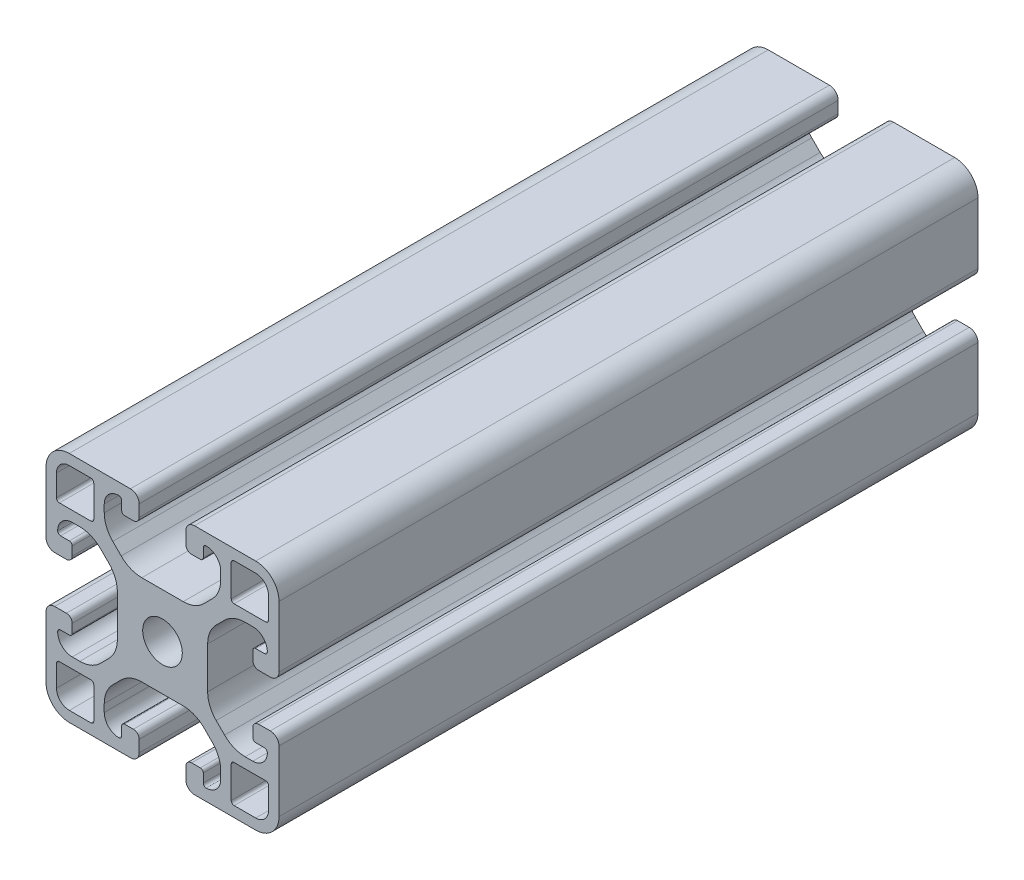
SolidWorks part; units mm, degrees
ref_plane "Plan de face" through (0, 0, 0) normal (0, 0, 1) x (1, 0, 0)
ref_plane "Plan de dessus" through (0, 0, 0) normal (0, 1, 0) x (1, 0, 0)
ref_plane "Plan de droite" through (0, 0, 0) normal (1, 0, 0) x (0, 0, -1)
ref_plane "Plan1" through (0, 0, -30) normal (0, 0, -1) x (-1, 0, 0)
sketch "Esquisse1" plane through (0, 0, -30) normal (0, 0, -1) x (-1, 0, 0)
  line L0 (-4.5, 15) -> (-4.5, 13.5)
  line L1 (-4, 13) -> (-2.5, 13)
  line L2 (-4.5, 10) -> (-5.8076, 10)
  line L3 (-9.3431, 11.4645) -> (-10.7855, 12.9069)
  line L4 (-12.25, 16.4424) -> (-12.25, 23.5576)
  line L5 (-10.7855, 27.0931) -> (-9.3431, 28.5355)
  line L6 (-5.8076, 30) -> (-4.5, 30)
  line L7 (-2.5, 27) -> (-4, 27)
  line L8 (-4.5, 26.5) -> (-4.5, 25)
  line L9 (-3.5, 24) -> (-1.5, 24)
  line L10 (0, 25.5) -> (0, 36)
  line L11 (-4, 40) -> (-14.5, 40)
  line L12 (-16, 38.5) -> (-16, 36.5)
  line L13 (-15, 35.5) -> (-13.5, 35.5)
  line L14 (-13, 36) -> (-13, 37.5)
  line L15 (-10, 35.5) -> (-10, 34.1924)
  line L16 (-11.4645, 30.6569) -> (-12.9069, 29.2145)
  line L17 (-16.4424, 27.75) -> (-23.5576, 27.75)
  line L18 (-27.0931, 29.2145) -> (-28.5355, 30.6569)
  line L19 (-30, 34.1924) -> (-30, 35.5)
  line L20 (-27, 37.5) -> (-27, 36)
  line L21 (-26.5, 35.5) -> (-25, 35.5)
  line L22 (-24, 36.5) -> (-24, 38.5)
  line L23 (-25.5, 40) -> (-36, 40)
  line L24 (-40, 36) -> (-40, 25.5)
  line L25 (-38.5, 24) -> (-36.5, 24)
  line L26 (-35.5, 25) -> (-35.5, 26.5)
  line L27 (-36, 27) -> (-37.5, 27)
  line L28 (-35.5, 30) -> (-34.1924, 30)
  line L29 (-30.6569, 28.5355) -> (-29.2145, 27.0931)
  line L30 (-27.75, 23.5576) -> (-27.75, 16.4424)
  line L31 (-29.2145, 12.9069) -> (-30.6569, 11.4645)
  line L32 (-34.1924, 10) -> (-35.5, 10)
  line L33 (-37.5, 13) -> (-36, 13)
  line L34 (-35.5, 13.5) -> (-35.5, 15)
  line L35 (-36.5, 16) -> (-38.5, 16)
  line L36 (-40, 14.5) -> (-40, 4)
  line L37 (-36, 0) -> (-25.5, 0)
  line L38 (-24, 1.5) -> (-24, 3.5)
  line L39 (-25, 4.5) -> (-26.5, 4.5)
  line L40 (-27, 4) -> (-27, 2.5)
  line L41 (-30, 4.5) -> (-30, 5.8076)
  line L42 (-28.5355, 9.3431) -> (-27.0931, 10.7855)
  line L43 (-23.5576, 12.25) -> (-16.4424, 12.25)
  line L44 (-12.9069, 10.7855) -> (-11.4645, 9.3431)
  line L45 (-10, 5.8076) -> (-10, 4.5)
  line L46 (-13, 2.5) -> (-13, 4)
  line L47 (-13.5, 4.5) -> (-15, 4.5)
  line L48 (-16, 3.5) -> (-16, 1.5)
  line L49 (-14.5, 0) -> (-4, 0)
  line L50 (0, 4) -> (0, 14.5)
  line L51 (-1.5, 16) -> (-3.5, 16)
  line L52 (-4, 1.8) -> (-7.7, 1.8)
  line L53 (-8.2, 2.3) -> (-8.2, 7.7)
  line L54 (-7.7, 8.2) -> (-2.3, 8.2)
  line L55 (-1.8, 7.7) -> (-1.8, 4)
  line L56 (-38.2, 4) -> (-38.2, 7.7)
  line L57 (-37.7, 8.2) -> (-32.3, 8.2)
  line L58 (-31.8, 7.7) -> (-31.8, 2.3)
  line L59 (-32.3, 1.8) -> (-36, 1.8)
  line L60 (-36, 38.2) -> (-32.3, 38.2)
  line L61 (-31.8, 37.7) -> (-31.8, 32.3)
  line L62 (-32.3, 31.8) -> (-37.7, 31.8)
  line L63 (-38.2, 32.3) -> (-38.2, 36)
  line L64 (-1.8, 36) -> (-1.8, 32.3)
  line L65 (-2.3, 31.8) -> (-7.7, 31.8)
  line L66 (-8.2, 32.3) -> (-8.2, 37.7)
  line L67 (-7.7, 38.2) -> (-4, 38.2)
  arc A0 (-4.5, 13.5) -> (-4, 13) centre (-4, 13.5) ccw
  arc A1 (-2.5, 13) -> (-2, 12.5) centre (-2.5, 12.5) cw
  arc A2 (-2, 12.5) -> (-4.5, 10) centre (-4.5, 12.5) cw
  arc A3 (-5.8076, 10) -> (-9.3431, 11.4645) centre (-5.8076, 15) cw
  arc A4 (-10.7855, 12.9069) -> (-12.25, 16.4424) centre (-7.25, 16.4424) cw
  arc A5 (-12.25, 23.5576) -> (-10.7855, 27.0931) centre (-7.25, 23.5576) cw
  arc A6 (-9.3431, 28.5355) -> (-5.8076, 30) centre (-5.8076, 25) cw
  arc A7 (-4.5, 30) -> (-2, 27.5) centre (-4.5, 27.5) cw
  arc A8 (-2, 27.5) -> (-2.5, 27) centre (-2.5, 27.5) cw
  arc A9 (-4, 27) -> (-4.5, 26.5) centre (-4, 26.5) ccw
  arc A10 (-4.5, 25) -> (-3.5, 24) centre (-3.5, 25) ccw
  arc A11 (-1.5, 24) -> (0, 25.5) centre (-1.5, 25.5) ccw
  arc A12 (0, 36) -> (-4, 40) centre (-4, 36) ccw
  arc A13 (-14.5, 40) -> (-16, 38.5) centre (-14.5, 38.5) ccw
  arc A14 (-16, 36.5) -> (-15, 35.5) centre (-15, 36.5) ccw
  arc A15 (-13.5, 35.5) -> (-13, 36) centre (-13.5, 36) ccw
  arc A16 (-13, 37.5) -> (-12.5, 38) centre (-12.5, 37.5) cw
  arc A17 (-12.5, 38) -> (-10, 35.5) centre (-12.5, 35.5) cw
  arc A18 (-10, 34.1924) -> (-11.4645, 30.6569) centre (-15, 34.1924) cw
  arc A19 (-12.9069, 29.2145) -> (-16.4424, 27.75) centre (-16.4424, 32.75) cw
  arc A20 (-23.5576, 27.75) -> (-27.0931, 29.2145) centre (-23.5576, 32.75) cw
  arc A21 (-28.5355, 30.6569) -> (-30, 34.1924) centre (-25, 34.1924) cw
  arc A22 (-30, 35.5) -> (-27.5, 38) centre (-27.5, 35.5) cw
  arc A23 (-27.5, 38) -> (-27, 37.5) centre (-27.5, 37.5) cw
  arc A24 (-27, 36) -> (-26.5, 35.5) centre (-26.5, 36) ccw
  arc A25 (-25, 35.5) -> (-24, 36.5) centre (-25, 36.5) ccw
  arc A26 (-24, 38.5) -> (-25.5, 40) centre (-25.5, 38.5) ccw
  arc A27 (-36, 40) -> (-40, 36) centre (-36, 36) ccw
  arc A28 (-40, 25.5) -> (-38.5, 24) centre (-38.5, 25.5) ccw
  arc A29 (-36.5, 24) -> (-35.5, 25) centre (-36.5, 25) ccw
  arc A30 (-35.5, 26.5) -> (-36, 27) centre (-36, 26.5) ccw
  arc A31 (-37.5, 27) -> (-38, 27.5) centre (-37.5, 27.5) cw
  arc A32 (-38, 27.5) -> (-35.5, 30) centre (-35.5, 27.5) cw
  arc A33 (-34.1924, 30) -> (-30.6569, 28.5355) centre (-34.1924, 25) cw
  arc A34 (-29.2145, 27.0931) -> (-27.75, 23.5576) centre (-32.75, 23.5576) cw
  arc A35 (-27.75, 16.4424) -> (-29.2145, 12.9069) centre (-32.75, 16.4424) cw
  arc A36 (-30.6569, 11.4645) -> (-34.1924, 10) centre (-34.1924, 15) cw
  arc A37 (-35.5, 10) -> (-38, 12.5) centre (-35.5, 12.5) cw
  arc A38 (-38, 12.5) -> (-37.5, 13) centre (-37.5, 12.5) cw
  arc A39 (-36, 13) -> (-35.5, 13.5) centre (-36, 13.5) ccw
  arc A40 (-35.5, 15) -> (-36.5, 16) centre (-36.5, 15) ccw
  arc A41 (-38.5, 16) -> (-40, 14.5) centre (-38.5, 14.5) ccw
  arc A42 (-40, 4) -> (-36, 0) centre (-36, 4) ccw
  arc A43 (-25.5, 0) -> (-24, 1.5) centre (-25.5, 1.5) ccw
  arc A44 (-24, 3.5) -> (-25, 4.5) centre (-25, 3.5) ccw
  arc A45 (-26.5, 4.5) -> (-27, 4) centre (-26.5, 4) ccw
  arc A46 (-27, 2.5) -> (-27.5, 2) centre (-27.5, 2.5) cw
  arc A47 (-27.5, 2) -> (-30, 4.5) centre (-27.5, 4.5) cw
  arc A48 (-30, 5.8076) -> (-28.5355, 9.3431) centre (-25, 5.8076) cw
  arc A49 (-27.0931, 10.7855) -> (-23.5576, 12.25) centre (-23.5576, 7.25) cw
  arc A50 (-16.4424, 12.25) -> (-12.9069, 10.7855) centre (-16.4424, 7.25) cw
  arc A51 (-11.4645, 9.3431) -> (-10, 5.8076) centre (-15, 5.8076) cw
  arc A52 (-10, 4.5) -> (-12.5, 2) centre (-12.5, 4.5) cw
  arc A53 (-12.5, 2) -> (-13, 2.5) centre (-12.5, 2.5) cw
  arc A54 (-13, 4) -> (-13.5, 4.5) centre (-13.5, 4) ccw
  arc A55 (-15, 4.5) -> (-16, 3.5) centre (-15, 3.5) ccw
  arc A56 (-16, 1.5) -> (-14.5, 0) centre (-14.5, 1.5) ccw
  arc A57 (-4, 0) -> (0, 4) centre (-4, 4) ccw
  arc A58 (0, 14.5) -> (-1.5, 16) centre (-1.5, 14.5) ccw
  arc A59 (-3.5, 16) -> (-4.5, 15) centre (-3.5, 15) ccw
  circle A60 centre (-20, 20) radius 3.4
  arc A61 (-1.8, 4) -> (-4, 1.8) centre (-4, 4) cw
  arc A62 (-7.7, 1.8) -> (-8.2, 2.3) centre (-7.7, 2.3) cw
  arc A63 (-8.2, 7.7) -> (-7.7, 8.2) centre (-7.7, 7.7) cw
  arc A64 (-2.3, 8.2) -> (-1.8, 7.7) centre (-2.3, 7.7) cw
  arc A65 (-36, 1.8) -> (-38.2, 4) centre (-36, 4) cw
  arc A66 (-38.2, 7.7) -> (-37.7, 8.2) centre (-37.7, 7.7) cw
  arc A67 (-32.3, 8.2) -> (-31.8, 7.7) centre (-32.3, 7.7) cw
  arc A68 (-31.8, 2.3) -> (-32.3, 1.8) centre (-32.3, 2.3) cw
  arc A69 (-38.2, 36) -> (-36, 38.2) centre (-36, 36) cw
  arc A70 (-32.3, 38.2) -> (-31.8, 37.7) centre (-32.3, 37.7) cw
  arc A71 (-31.8, 32.3) -> (-32.3, 31.8) centre (-32.3, 32.3) cw
  arc A72 (-37.7, 31.8) -> (-38.2, 32.3) centre (-37.7, 32.3) cw
  arc A73 (-4, 38.2) -> (-1.8, 36) centre (-4, 36) cw
  arc A74 (-1.8, 32.3) -> (-2.3, 31.8) centre (-2.3, 32.3) cw
  arc A75 (-7.7, 31.8) -> (-8.2, 32.3) centre (-7.7, 32.3) cw
  arc A76 (-8.2, 37.7) -> (-7.7, 38.2) centre (-7.7, 37.7) cw
extrude "Boss.-Extru.1" add sketch "Esquisse1" against normal blind 120
